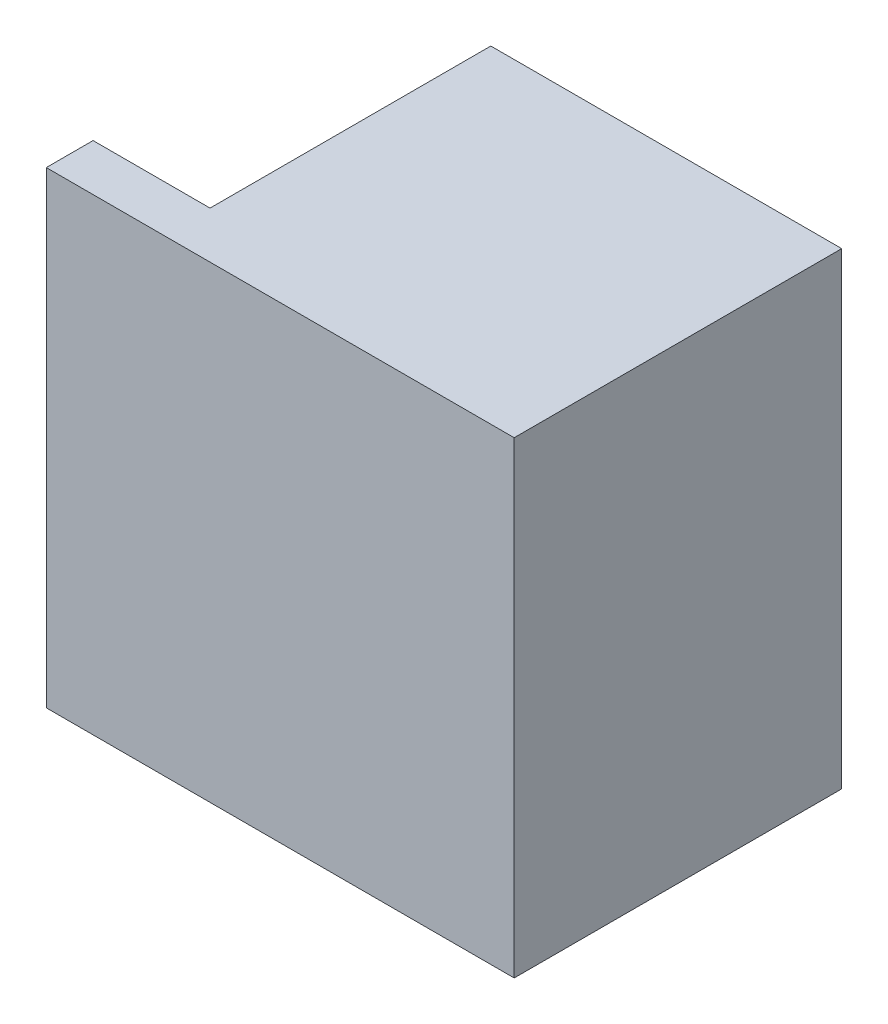
SolidWorks part; units mm, degrees
ref_plane "Front Plane" through (0, 0, 0) normal (0, 0, 1) x (1, 0, 0)
ref_plane "Top Plane" through (0, 0, 0) normal (0, 1, 0) x (1, 0, 0)
ref_plane "Right Plane" through (0, 0, 0) normal (1, 0, 0) x (0, 0, -1)
sketch "Sketch1" plane through (0, 0, 0) normal (0, 0, 1) x (1, 0, 0)
  line L1 (10, 10) -> (-10, 10)
  line L2 (10, 10) -> (10, -10)
  line L3 (10, -10) -> (-10, -10)
  line L4 (-10, 10) -> (-10, -10)
  line L5 (10, 10) -> (-10, -10) construction
  line L6 (10, -10) -> (-10, 10) construction
  point P0 (0, 0)
  dimension "D1" = 20
  dimension "D2" = 20
extrude "Boss-Extrude1" add sketch "Sketch1" along normal blind 14
sketch "Sketch2" plane through (0, 0, 0) normal (0, 0, -1) x (-1, 0, 0)
  line L0 (10, 10) -> (10, -10) construction
  line L1 (3, 8) -> (-8, 8)
  line L2 (10, 10) -> (10, -10)
  line L3 (-5, -8) -> (-8, -8)
  line L4 (-8, 8) -> (-8, -8)
  line L6 (-10, 10) -> (10, 10) construction
  line L7 (-10, -10) -> (-10, 10) construction
  line L8 (10, -10) -> (-10, -10) construction
  line L9 (-5, -8) -> (-5, -10)
  line L10 (10, -10) -> (-5, -10)
  line L11 (5, 3) -> (5, 10)
  line L12 (10, 10) -> (5, 10)
  line L13 (3, 8) -> (3, 3)
  line L14 (3, 3) -> (5, 3)
  dimension "D1" = 2
  dimension "D2" = 2
  dimension "D3" = 2
  dimension "D4" = 5
  dimension "D5" = 5
  dimension "D6" = 2
  dimension "D7" = 5
extrude "Cut-Extrude1" cut sketch "Sketch2" against normal offset from surface (12 mm away) 2 up to face at (0, 0, 14)
sketch "Sketch5" plane through (0, 0, 0) normal (0, 0, -1) x (-1, 0, 0)
  line L0 (-8, 35) -> (-8, 10)
  line L1 (-8, 35) -> (3, 35)
  line L2 (3, 35) -> (3, 30)
  line L3 (3, 30) -> (5, 30)
  line L4 (5, 30) -> (5, 37)
  line L5 (5, 37) -> (-10, 37)
  line L6 (-10, 10) -> (5, 10) construction
  line L7 (-8, 10) -> (-10, 10)
  line L8 (-10, 10) -> (-10, 37)
  line L9 (5, 10) -> (5, 3) construction
  line L10 (3, 3) -> (3, 8) construction
  line L11 (-8, 8) -> (-8, -8) construction
  dimension "D1" = 25
